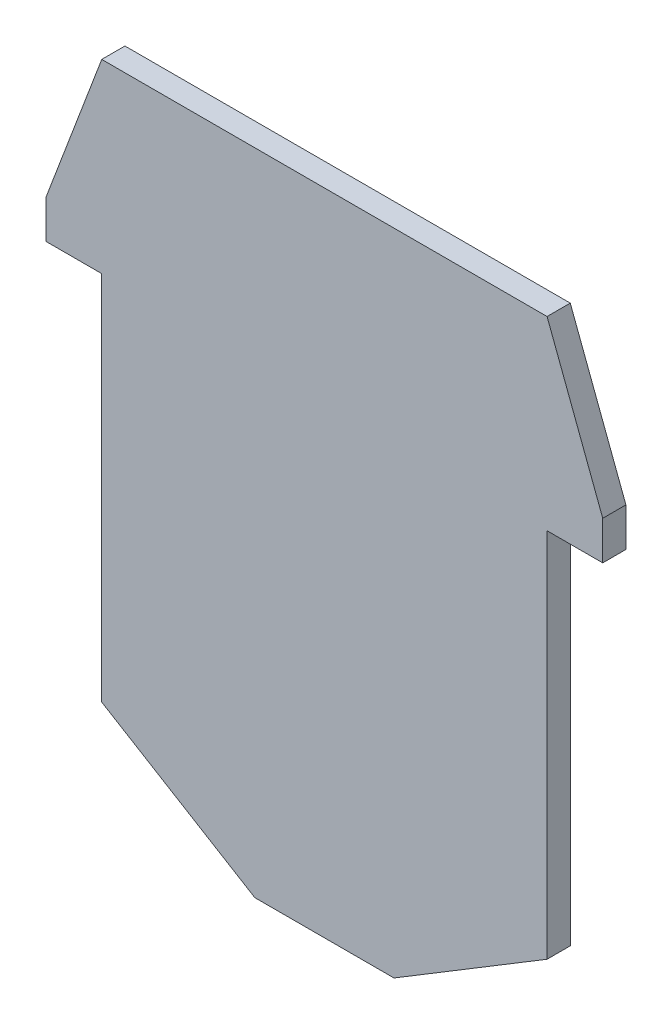
SolidWorks part; units mm, degrees
ref_plane "Front Plane" through (0, 0, 0) normal (0, 0, 1) x (1, 0, 0)
ref_plane "Top Plane" through (0, 0, 0) normal (0, 1, 0) x (1, 0, 0)
ref_plane "Right Plane" through (0, 0, 0) normal (1, 0, 0) x (0, 0, -1)
sketch "Sketch1" plane through (0, 0, 0) normal (0, 0, 1) x (1, 0, 0)
  line L0 (25.509, 41.6766) -> (25.509, -78.3234) construction
  line L1 (-34.491, 41.6766) -> (85.509, 41.6766)
  line L2 (-34.491, 41.6766) -> (-34.491, -78.3234)
  line L3 (-34.491, -78.3234) -> (85.509, -78.3234)
  line L4 (85.509, 41.6766) -> (85.509, -78.3234)
  line L5 (-34.491, 1.6766) -> (85.509, 1.6766)
  line L6 (-22.491, 41.6766) -> (-34.491, 10.003)
  line L7 (-34.491, 10.003) -> (-34.491, 1.6766)
  line L8 (-22.491, 1.6766) -> (-22.491, -78.3234)
  line L9 (-22.491, -78.3234) -> (10.509, -98.3234)
  line L10 (10.509, -98.3234) -> (40.509, -98.3234)
  line L11 (25.509, -98.3234) -> (25.509, 41.6766)
  line L12 (73.509, 41.6766) -> (-22.491, 41.6766)
  line L13 (73.509, -78.3234) -> (40.509, -98.3234)
  line L14 (73.509, 1.6766) -> (73.509, -78.3234)
  line L15 (73.509, 41.6766) -> (85.509, 10.003)
  line L16 (73.509, 1.6766) -> (85.509, 1.6766)
  line L17 (85.509, 10.003) -> (85.509, 1.6766)
  dimension "D1" = 120
  dimension "D2" = 120
  dimension "D3" = 80
  dimension "D4" = 12
  dimension "D5" = 30
  dimension "D6" = 140
extrude "Boss-Extrude1" add sketch "Sketch1" along normal blind 5 contours L5 L11 L1 L6 L2 | L15 L1 L11 L5 L4 | L3 L11 L5 L8 | L14 L5 L11 L3 | L10 L11 L3 L9 | L13 L3 L11 L10
